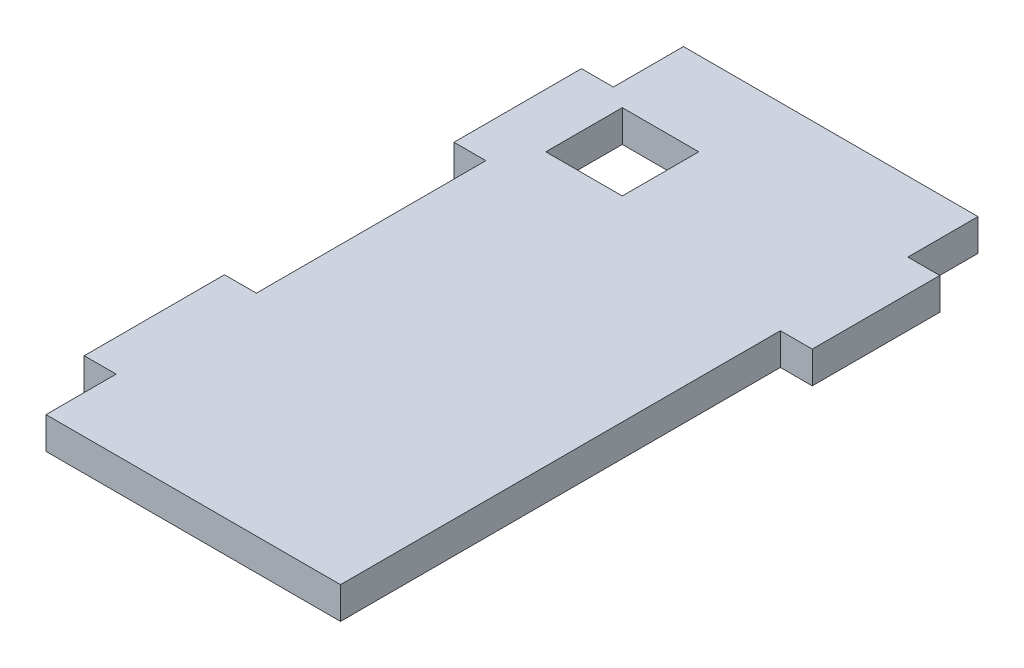
SolidWorks part; units mm, degrees
ref_plane "Front Plane" through (0, 0, 0) normal (0, 0, 1) x (1, 0, 0)
ref_plane "Top Plane" through (0, 0, 0) normal (0, 1, 0) x (1, 0, 0)
ref_plane "Right Plane" through (0, 0, 0) normal (1, 0, 0) x (0, 0, -1)
sketch "Sketch1" plane through (0, 0, 0) normal (0, 1, 0) x (1, 0, 0)
  line L0 (0, 113.03) -> (0, 127)
  line L1 (0, 0) -> (58.674, 0)
  line L2 (0, 0) -> (0, 13.97)
  line L3 (0, 127) -> (58.674, 127)
  line L4 (58.674, 0) -> (58.674, 87.63)
  line L5 (58.674, 113.03) -> (65.024, 113.03)
  line L7 (58.674, 87.63) -> (65.024, 87.63)
  line L8 (65.024, 113.03) -> (65.024, 87.63)
  line L9 (0, 113.03) -> (-6.35, 113.03)
  line L10 (58.674, 113.03) -> (58.674, 127)
  line L11 (0, 87.63) -> (-6.35, 87.63)
  line L12 (-6.35, 113.03) -> (-6.35, 87.63)
  line L13 (0, 41.91) -> (-6.35, 41.91)
  line L15 (0, 13.97) -> (-6.35, 13.97)
  line L16 (-6.35, 41.91) -> (-6.35, 13.97)
  line L17 (0, 41.91) -> (0, 87.63)
  dimension "D1" = 127
  dimension "D2" = 58.674
  dimension "D3" = 6.35
  dimension "D4" = 6.35
  dimension "D5" = 25.4
  dimension "D6" = 25.4
  dimension "D7" = 13.97
  dimension "D8" = 13.97
  dimension "D9" = 13.97
  dimension "D10" = 27.94
  dimension "D11" = 6.35
extrude "Boss-Extrude1" add sketch "Sketch1" along normal blind 6.35
sketch "Sketch4" plane through (0, 6.35, 0) normal (0, 1, 0) x (1, 0, 0)
  line L0 (0, 127) -> (0, 113.03) construction
  line L1 (4.445, 95.123) -> (19.685, 95.123)
  line L2 (4.445, 95.123) -> (4.445, 110.363)
  line L3 (4.445, 110.363) -> (19.685, 110.363)
  line L4 (19.685, 95.123) -> (19.685, 110.363)
  line L5 (58.674, 127) -> (0, 127) construction
  dimension "D1" = 15.24
  dimension "D2" = 15.24
  dimension "D3" = 4.445
  dimension "D4" = 16.637
extrude "Cut-Extrude1" cut sketch "Sketch4" against normal blind 6.35
